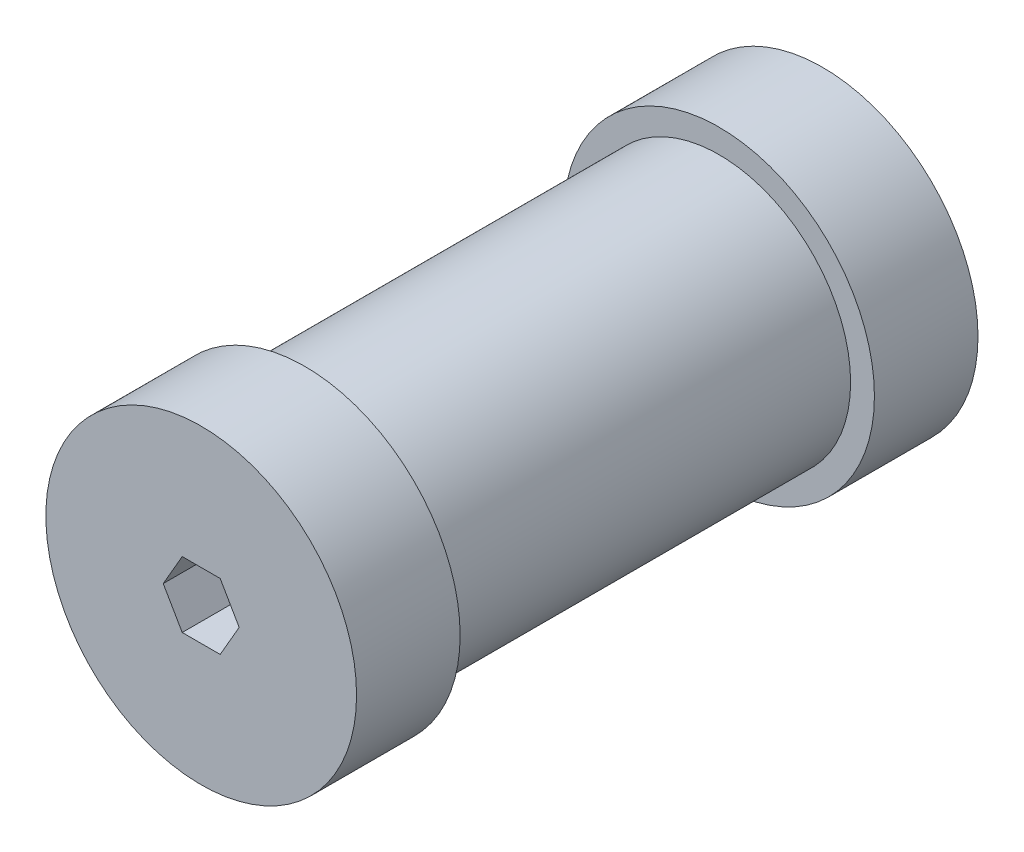
SolidWorks part; units mm, degrees
ref_plane "Alzado" through (0, 0, 0) normal (0, 0, 1) x (1, 0, 0)
ref_plane "Planta" through (0, 0, 0) normal (0, 1, 0) x (1, 0, 0)
ref_plane "Vista lateral" through (0, 0, 0) normal (1, 0, 0) x (0, 0, -1)
sketch "Croquis1" plane through (0, 0, 0) normal (0, 1, 0) x (1, 0, 0)
  line L0 (0, 55.3933) -> (0, -64.6067) construction
  line L1 (0, 55.3933) -> (-30, 55.3933)
  line L2 (-30, 55.3933) -> (-30, 35.3933)
  line L3 (-30, 35.3933) -> (-25.4, 35.3933)
  line L4 (-25.4, 35.3933) -> (-25.4, -44.6067)
  line L5 (-25.4, -44.6067) -> (-30, -44.6067)
  line L6 (-30, -44.6067) -> (-30, -64.6067)
  line L7 (-30, -64.6067) -> (0, -64.6067)
  line L8 (0, -64.6067) -> (0, 55.3933)
  dimension "D1" = 80
  dimension "D2" = 20
  dimension "D3" = 20
  dimension "D4" = 30
  dimension "D5" = 25.4
revolve "Revolución1" add sketch "Croquis1" angle 360 about L8
sketch "Croquis2" plane through (0, 0, -55.3933) normal (0, 0, -1) x (-1, 0, 0)
  line L1 (7.3323, 0) -> (3.6662, 6.35)
  line L2 (3.6662, 6.35) -> (-3.6662, 6.35)
  line L3 (-3.6662, 6.35) -> (-7.3323, 0)
  line L4 (-7.3323, 0) -> (-3.6662, -6.35)
  line L5 (-3.6662, -6.35) -> (3.6662, -6.35)
  line L6 (3.6662, -6.35) -> (7.3323, 0)
  circle A0 centre (0, 0) radius 6.35 construction
  dimension "D1" = 12.7
extrude "Cortar-Extruir1" cut sketch "Croquis2" against normal through all
